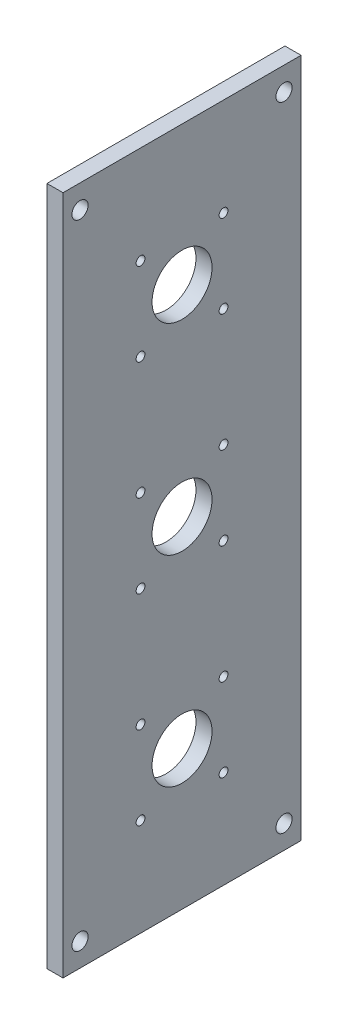
SolidWorks part; units mm, degrees
ref_plane "Front Plane" through (0, 0, 0) normal (1, 0, 0) x (0, 1, 0)
ref_plane "Top Plane" through (0, 0, 0) normal (0, 0, 1) x (0, 1, 0)
ref_plane "Right Plane" through (0, 0, 0) normal (0, 1, 0) x (-1, 0, 0)
sketch "Sketch1" plane through (0, 0, 0) normal (1, 0, 0) x (0, 1, 0)
  line L0 (0, -55) -> (0, 55) construction
  line L1 (-127, -44.45) -> (127, -44.45)
  line L2 (-127, -44.45) -> (-127, 44.45)
  line L3 (-127, 44.45) -> (127, 44.45)
  line L4 (127, -44.45) -> (127, 44.45)
  line L5 (-127, -44.45) -> (127, 44.45) construction
  line L6 (-127, 44.45) -> (127, -44.45) construction
  point P0 (0, 0)
  point P6 (-118.2625, -38.1)
  point P7 (-118.2625, -22.225)
  point P8 (-118.2625, -6.35)
  point P11 (-118.2625, 6.35)
  point P12 (-118.2625, 22.225)
  point P13 (-118.2625, 38.1)
  point P14 (118.2625, -38.1)
  point P15 (118.2625, -22.225)
  point P16 (118.2625, -6.35)
  point P17 (118.2625, 6.35)
  point P18 (118.2625, 22.225)
  point P19 (118.2625, 38.1)
  dimension "D1" = 254
  dimension "D2" = 88.9
  dimension "D3" = 118.2625
  dimension "D4" = 6.35
  dimension "D5" = 3
  dimension "D6" = 2
extrude "Boss-Extrude1" add sketch "Sketch1" against normal blind 6
sketch "Sketch2" plane through (0, 0, 0) normal (1, 0, 0) x (0, 1, 0)
  line L0 (-127, -44.45) -> (127, -44.45) construction
  line L1 (0, -3.3) -> (0, 3.3) construction
  point P5 (-118.2625, 38.1)
  point P6 (-118.2625, -38.1)
  point P9 (118.2625, -38.1)
  point P17 (118.2625, 38.1)
  dimension "D1" = 6.35
  dimension "D2" = 118.2625
hole_wizard "#10 Clearance Hole1" positions "Sketch2" profile "Sketch3" hole size "#10" standard "ANSI Inch" end condition up to next
sketch "Sketch3" plane through (0, 118.2625, 38.1) normal (0, 1, 0) x (0, 0, -1)
  line L0 (0, 0) -> (0, 6)
  line L1 (0, 6) -> (3.0226, 6)
  line L2 (3.0226, 6) -> (3.0226, 0)
  line L5 (3.0226, 0) -> (0, 0)
  line L11 (0, -6.35) -> (0, 107.95) construction
  dimension "Thru Hole Dia." = 6.0452
  dimension "Thru Hole Depth" = 6
sketch "Sketch4" plane through (0, 0, 0) normal (1, 0, 0) x (0, 1, 0)
  line L0 (0, 15.5) -> (0, -15.5) construction
  line L1 (-15.5, 15.5) -> (15.5, 15.5) construction
  line L2 (-15.5, 15.5) -> (-15.5, -15.5) construction
  line L3 (-15.5, -15.5) -> (15.5, -15.5) construction
  line L4 (15.5, 15.5) -> (15.5, -15.5) construction
  line L5 (-15.5, 15.5) -> (15.5, -15.5) construction
  line L6 (-15.5, -15.5) -> (15.5, 15.5) construction
  line L7 (-15.5, 0) -> (15.5, 0) construction
  circle A0 centre (0, 0) radius 11.2
  circle A1 centre (-15.5, 15.5) radius 1.65
  circle A2 centre (15.5, 15.5) radius 1.65
  circle A3 centre (15.5, -15.5) radius 1.65
  circle A4 centre (-15.5, -15.5) radius 1.65
  circle A5 centre (75, 0) radius 11.2
  circle A6 centre (59.5, 15.5) radius 1.65
  circle A7 centre (90.5, 15.5) radius 1.65
  circle A8 centre (90.5, -15.5) radius 1.65
  circle A9 centre (59.5, -15.5) radius 1.65
  circle A10 centre (-75, 0) radius 11.2
  circle A11 centre (-90.5, -15.5) radius 1.65
  circle A12 centre (-59.5, -15.5) radius 1.65
  circle A13 centre (-59.5, 15.5) radius 1.65
  circle A14 centre (-90.5, 15.5) radius 1.65
  point P0 (0, 0)
  point P7 (-15.5, 15.5)
  point P8 (15.5, 15.5)
  point P9 (15.5, -15.5)
  point P10 (-15.5, -15.5)
  dimension "D3" = 22.4
  dimension "D4" = 3.3
  dimension "D1" = 31
  dimension "D2" = 31
  dimension "D5" = 2
  dimension "D6" = 2
extrude "Cut-Extrude1" cut sketch "Sketch4" along direction (-1, 0, 0) on the side against the normal through all
equation "\"size\"= 2"
equation "\"height\"= 44.45 * \"size\""
equation "\"D2@Sketch1\"=\"height\""
